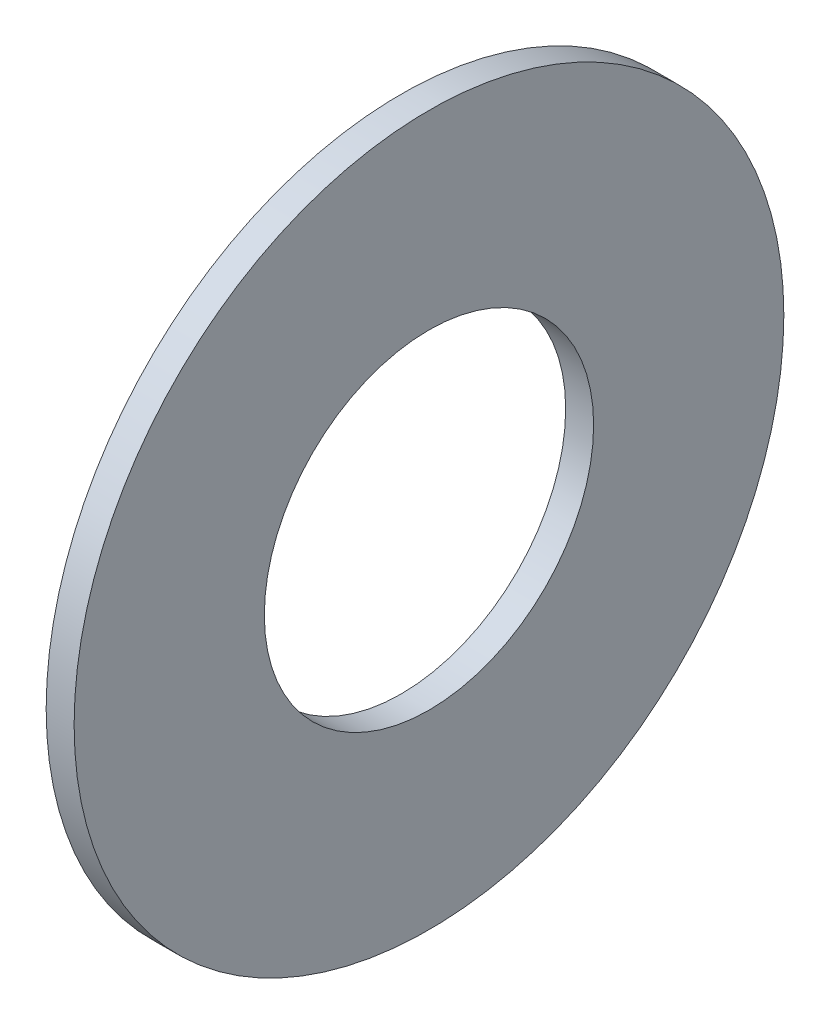
SolidWorks part; units mm, degrees
ref_plane "Front Plane" through (0, 0, 0) normal (0, 0, 1) x (1, 0, 0)
ref_plane "Top Plane" through (0, 0, 0) normal (0, 1, 0) x (1, 0, 0)
ref_plane "Right Plane" through (0, 0, 0) normal (1, 0, 0) x (0, 0, -1)
sketch "Sketch1" plane through (0, 0, 0) normal (1, 0, 0) x (0, 0, -1)
  line L0 (4.7625, 0) -> (-4.7625, 0) construction
  circle A0 centre (0, 0) radius 10.3187 construction
  circle A1 centre (0, 0) radius 4.7879 construction
  circle A2 centre (0, 0) radius 4.7625
  point P9 (0, 0)
  dimension "OD" = 20.6375
  dimension "ID" = 9.5758
  dimension "For Shaft Diameter" = 9.525
sketch "Sketch2" plane through (0, 0, 0) normal (0, 0, 1) x (1, 0, 0)
  line L0 (0.4064, 0) -> (-0.4064, 0) construction
  line L2 (0.4064, -10.3187) -> (-0.4064, -10.3187) construction
  line L3 (0.4064, -10.3187) -> (0.4064, 10.3187) construction
  line L4 (0.4064, 10.3187) -> (-0.4064, 10.3187) construction
  line L5 (-0.4064, -10.3187) -> (-0.4064, 10.3187) construction
  line L6 (0, 10.3187) -> (0, -10.3187) construction
  line L7 (0.4064, 0) -> (-0.4064, 0) construction
  line L8 (0, -10.3187) -> (0, 10.3187) construction
  point P0 (0, 0)
  point P4 (0, 0)
  dimension "Thickness" = 0.8128
  dimension "D1" = 20.6375
sketch "Sketch5" plane through (0, 0, 0) normal (1, 0, 0) x (0, 0, -1)
  circle A0 centre (0, 0) radius 4.7879 construction
  circle A1 centre (0, 0) radius 10.3187 construction
  circle A3 centre (0, 0) radius 4.7879
  circle A5 centre (0, 0) radius 10.3187
extrude "Boss-Extrude1" add sketch "Sketch5" along normal mid plane 0.8128
equation "\"D1@Boss-Extrude1\"= \"Thickness@Sketch2\""
equation "\"D1@Sketch2\"=\"OD@Sketch1\""
